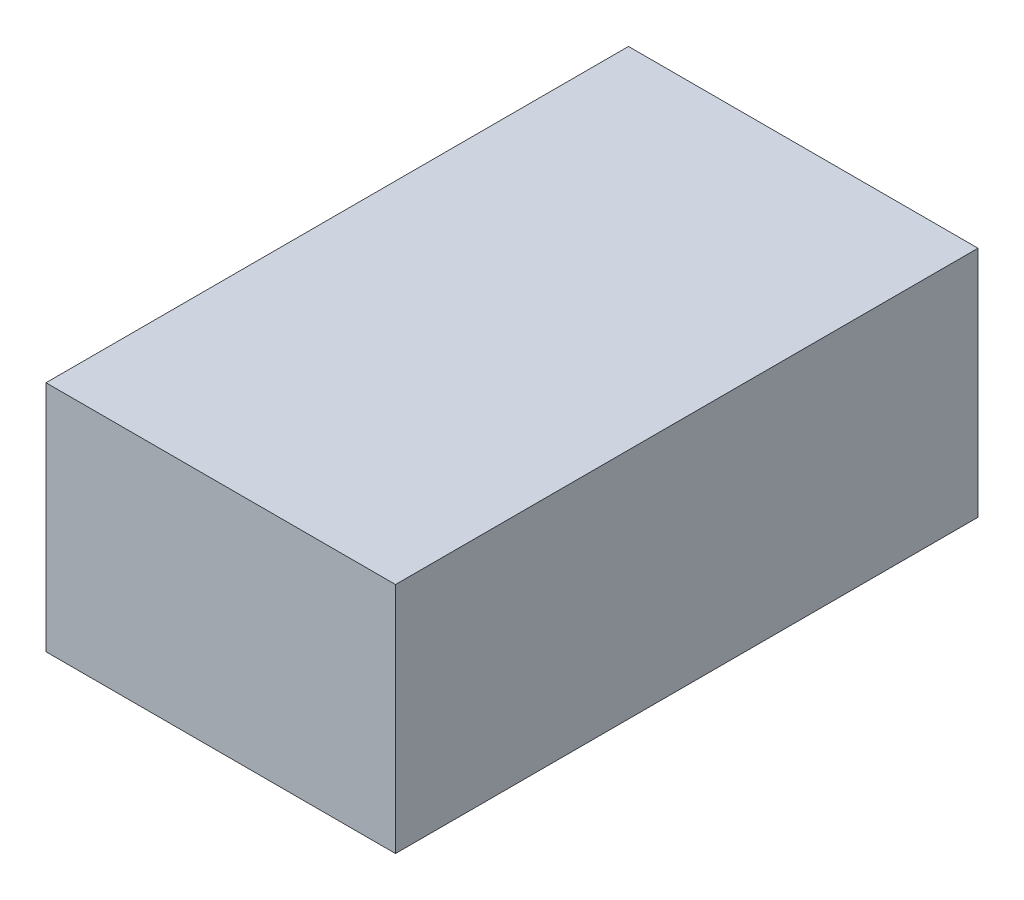
SolidWorks part; units mm, degrees
ref_plane "前视基准面" through (0, 0, 0) normal (0, 0, 1) x (1, 0, 0)
ref_plane "上视基准面" through (0, 0, 0) normal (0, 1, 0) x (1, 0, 0)
ref_plane "右视基准面" through (0, 0, 0) normal (1, 0, 0) x (0, 0, -1)
other "Configuration Table"
sketch "草图1" plane through (0, 0, 0) normal (0, 0, 1) x (1, 0, 0)
  line L1 (-30, 20) -> (30, 20)
  line L2 (-30, 20) -> (-30, -20)
  line L3 (-30, -20) -> (30, -20)
  line L4 (30, 20) -> (30, -20)
  line L5 (-30, 20) -> (30, -20) construction
  line L6 (-30, -20) -> (30, 20) construction
  point P0 (0, 0)
  dimension "D1" = 60
  dimension "D2" = 40
extrude "凸台-拉伸1" add sketch "草图1" along normal blind 100
sketch "草图2" plane through (0, 0, 0) normal (0, 0, -1) x (-1, 0, 0)
  circle A0 centre (0, 0) radius 4
  dimension "D1" = 8
extrude "切除-拉伸1" cut sketch "草图2" against normal blind 10
